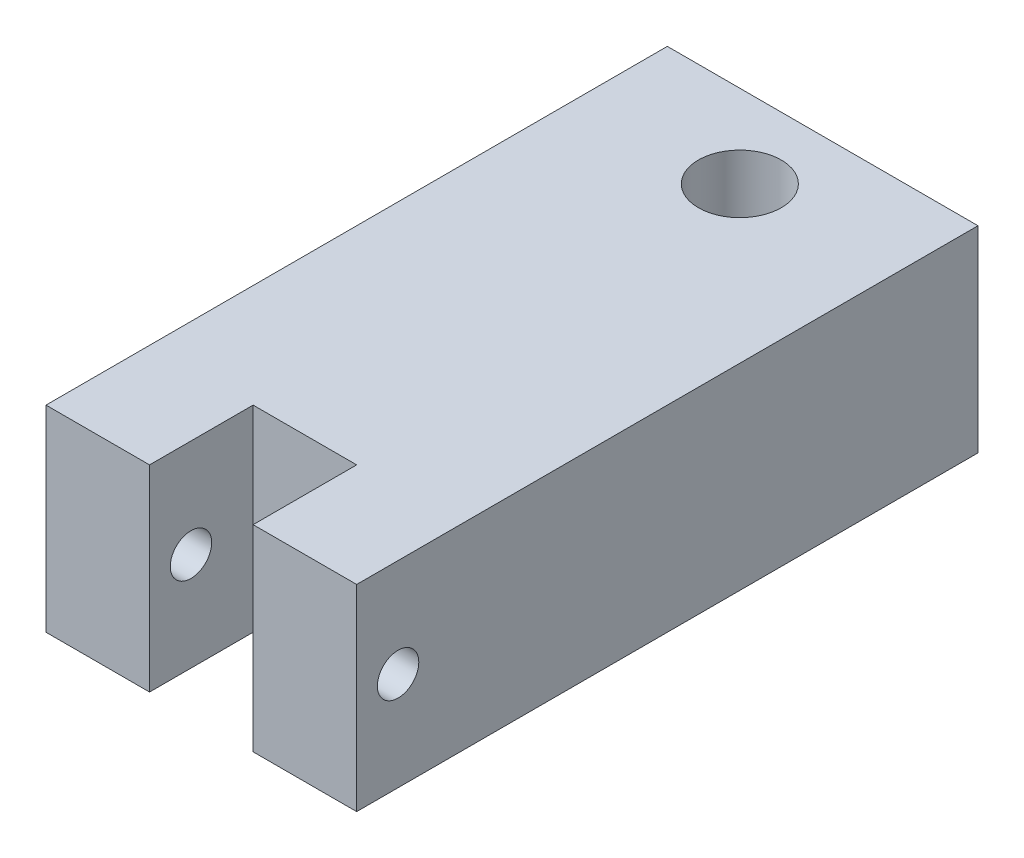
SolidWorks part; units mm, degrees
material "PE High Density"
ref_plane "Front Plane" through (0, 0, 0) normal (0, 0, 1) x (1, 0, 0)
ref_plane "Top Plane" through (0, 0, 0) normal (0, 1, 0) x (1, 0, 0)
ref_plane "Right Plane" through (0, 0, 0) normal (1, 0, 0) x (0, 0, -1)
sketch "Sketch1" plane through (0, 0, 0) normal (0, 1, 0) x (1, 0, 0)
  line L0 (72.9996, 104.0008) -> (97.9996, 104.0008)
  line L1 (-52.0004, 104.0008) -> (22.9996, 104.0008)
  line L2 (-52.0004, 104.0008) -> (-52.0004, -195.9992)
  line L3 (-52.0004, -195.9992) -> (22.9996, -195.9992)
  line L4 (97.9996, 104.0008) -> (97.9996, -195.9992)
  line L5 (-52.0004, 104.0008) -> (97.9996, -195.9992) construction
  line L6 (0, 0) -> (97.9996, 104.0008) construction
  line L15 (72.9996, -195.9992) -> (97.9996, -195.9992)
  line L16 (22.9996, 104.0008) -> (72.9996, 104.0008)
  line L17 (22.9996, -195.9992) -> (72.9996, -195.9992)
  point P0 (0, 0)
  dimension "D1" = 150
  dimension "D2" = 300
extrude "Boss-Extrude1" add sketch "Sketch1" along normal blind 95
sketch "Sketch3" plane through (0, 95, 0) normal (0, 1, 0) x (1, 0, 0)
  line L0 (97.9996, 104.0008) -> (-52.0004, 104.0008) construction
  line L1 (97.9996, -195.9992) -> (97.9996, 104.0008) construction
  circle A0 centre (22.9996, 64.0008) radius 20
  dimension "D1" = 40
  dimension "D2" = 40
  dimension "D3" = 75
extrude "Cut-Extrude2" cut sketch "Sketch3" against normal blind 327
sketch "Sketch4" plane through (97.9996, 0, 0) normal (1, 0, 0) x (0, 0, -1)
  line L0 (-195.9992, 95) -> (-195.9992, 0) construction
  circle A0 centre (-175.9992, 47.5) radius 10
  dimension "D1" = 20
  dimension "D2" = 20
extrude "Cut-Extrude3" cut sketch "Sketch4" against normal blind 260
sketch "Sketch5" plane through (0, 0, 195.9992) normal (0, 0, 1) x (1, 0, 0)
  line L0 (-52.0004, 0) -> (97.9996, 0) construction
  line L1 (-2.0004, 95.1252) -> (47.9996, 95.1252)
  line L2 (-2.0004, 95.1252) -> (-2.0004, 0)
  line L3 (-2.0004, 0) -> (47.9996, 0)
  line L4 (47.9996, 95.1252) -> (47.9996, 0)
  line L5 (-2.0004, 95.1252) -> (47.9996, 0) construction
  line L6 (-2.0004, 0) -> (47.9996, 95.1252) construction
  line L7 (-52.0004, 95) -> (-52.0004, 0) construction
  point P0 (22.9996, 47.5626)
  dimension "D1" = 50
  dimension "D2" = 50
extrude "Cut-Extrude4" cut sketch "Sketch5" against normal blind 50
scale "Scale1" scale about centroid uniform scaling yes scale factor 0.75
